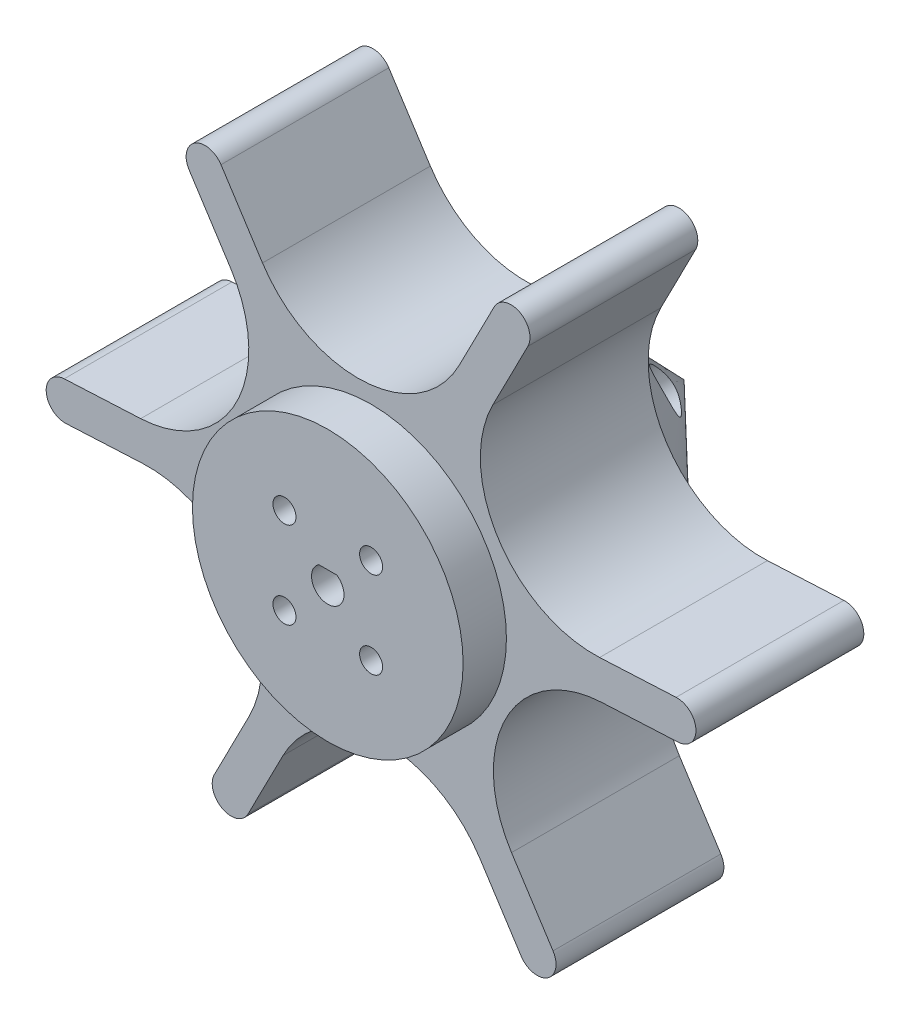
SolidWorks part; units mm, degrees
ref_plane "Front Plane" through (0, 0, 0) normal (0, 0, 1) x (1, 0, 0)
ref_plane "Top Plane" through (0, 0, 0) normal (0, 1, 0) x (1, 0, 0)
ref_plane "Right Plane" through (0, 0, 0) normal (1, 0, 0) x (0, 0, -1)
sketch "Sketch1" plane through (0, 0, 0) normal (0, 0, 1) x (1, 0, 0)
  line L0 (-33.6058, 45.6534) -> (-25.9397, 33.7658)
  line L1 (-30.6644, 47.5503) -> (-56.5119, -2.781) construction
  line L2 (-56.5119, -2.781) -> (-25.8475, -50.3313) construction
  line L3 (-25.8475, -50.3313) -> (30.6644, -47.5503) construction
  line L4 (30.6644, -47.5503) -> (56.5119, 2.781) construction
  line L5 (56.5119, 2.781) -> (25.8475, 50.3313) construction
  line L6 (25.8475, 50.3313) -> (-30.6644, 47.5503) construction
  line L7 (-27.723, 49.4471) -> (-20.0569, 37.5596)
  line L8 (22.7341, 51.9302) -> (16.2722, 39.3474)
  line L9 (28.961, 48.7324) -> (22.4991, 36.1496)
  line L10 (56.3399, 6.2768) -> (42.2119, 5.5815)
  line L11 (56.684, -0.7147) -> (42.556, -1.41)
  line L12 (33.6058, -45.6534) -> (25.9397, -33.7658)
  line L13 (27.723, -49.4471) -> (20.0569, -37.5596)
  line L14 (-22.7341, -51.9302) -> (-16.2722, -39.3474)
  line L15 (-28.961, -48.7324) -> (-22.4991, -36.1496)
  line L16 (-56.3399, -6.2768) -> (-42.2119, -5.5815)
  line L17 (-56.684, 0.7147) -> (-42.556, 1.41)
  circle A0 centre (41.1797, 26.5562) radius 21 construction
  circle A1 centre (43.5882, -22.3846) radius 21 construction
  circle A2 centre (2.4085, -48.9408) radius 21 construction
  circle A3 centre (-41.1797, -26.5562) radius 21 construction
  circle A4 centre (-43.5882, 22.3846) radius 21 construction
  circle A5 centre (-2.4085, 48.9408) radius 21 construction
  circle A6 centre (0, 0) radius 49 construction
  circle A7 centre (-30.6644, 47.5503) radius 3.5
  circle A8 centre (25.8475, 50.3313) radius 3.5
  circle A9 centre (56.5119, 2.781) radius 3.5
  circle A10 centre (30.6644, -47.5503) radius 3.5
  circle A11 centre (-25.8475, -50.3313) radius 3.5
  circle A12 centre (-56.5119, -2.781) radius 3.5
  arc A13 (-42.556, 1.41) -> (-25.9397, 33.7658) centre (-43.5882, 22.3846) ccw
  arc A14 (-20.0569, 37.5596) -> (16.2722, 39.3474) centre (-2.4085, 48.9408) ccw
  arc A15 (22.4991, 36.1496) -> (42.2119, 5.5815) centre (41.1797, 26.5562) ccw
  arc A16 (42.556, -1.41) -> (25.9397, -33.7658) centre (43.5882, -22.3846) ccw
  arc A17 (20.0569, -37.5596) -> (-16.2722, -39.3474) centre (2.4085, -48.9408) ccw
  arc A18 (-22.4991, -36.1496) -> (-42.2119, -5.5815) centre (-41.1797, -26.5562) ccw
  point P25 (0, 0)
  point P36 (0, 0)
  point P60 (0, 0)
  point P77 (0, 0)
  dimension "D2" = 42
  dimension "D4" = 7
  dimension "D1" = 6
  dimension "D3" = 6
  dimension "D5" = 6
  dimension "D6" = 6
extrude "Boss-Extrude1" add sketch "Sketch1" along normal blind 21 contours A18 L15 A11 L14 A17 L13 A10 L12 A16 L11 A9 L10 A15 L9 A8 L8 A14 L7 A7 L0 A13 L17 A12 L16 | A12 | A7 | A8 | A9 | A10 | A11
ref_plane "Plane1" through (0, 0, 0) normal (0.0492, -0.9988, 0) x (-0.9988, -0.0492, 0)
sketch "Sketch3" plane through (0, 0, 0) normal (0.0492, -0.9988, 0) x (-0.9988, -0.0492, 0)
  line L0 (0, 0) -> (-28, 0)
  line L1 (-28, 0) -> (0, 26.8135)
  line L2 (0, 26.8135) -> (0, 0)
  dimension "D1" = 28
revolve "Revolve1" add sketch "Sketch3" angle 360 about L2
sketch "Sketch4" plane through (0, 0, 21) normal (0, 0, 1) x (1, 0, 0)
  circle A0 centre (0, 0) radius 25
  dimension "D1" = 50
extrude "Boss-Extrude2" add sketch "Sketch4" along normal blind 18
sketch "Sketch5" plane through (0, 0, 39) normal (0, 0, 1) x (1, 0, 0)
  line L0 (-1.6583, 2.5) -> (1.6583, 2.5)
  arc A0 (-1.6583, 2.5) -> (1.6583, 2.5) centre (0, 0) ccw
  dimension "D1" = 6
  dimension "D2" = 2.5
extrude "Cut-Extrude2" cut sketch "Sketch5" against normal blind 20
ref_plane "Plane2" through (-1.2288, 24.9698, 0) normal (-0.0492, 0.9988, 0) x (0.9988, 0.0492, 0)
ref_plane "Plane5" through (1.2288, -24.9698, 0) normal (0.0492, -0.9988, 0) x (-0.9988, -0.0492, 0)
sketch "Sketch7" plane through (0, 0, 39) normal (0, 0, 1) x (1, 0, 0)
  line L0 (0, 12.9158) -> (0, -15.3556) construction
  line L1 (-12.6694, 0) -> (16.084, 0) construction
  circle A0 centre (-8, 8) radius 2.125
  circle A1 centre (8, 8) radius 2.125
  circle A2 centre (8, -8) radius 2.125
  circle A3 centre (-8, -8) radius 2.125
  dimension "D1" = 4.25
  dimension "D2" = 8
  dimension "D3" = 8
extrude "Cut-Extrude3" cut sketch "Sketch7" against normal through all
sketch "Sketch9" plane through (0, 0, 0) normal (0, 0, -1) x (-1, 0, 0)
  line L0 (0, 0) -> (24.2952, 0) construction
  line L1 (0, 0) -> (0, 21.4598) construction
  circle A1 centre (-8, 8) radius 2.125 construction
  circle A5 centre (-8, 8) radius 2.125 construction
  circle A8 centre (-8, 8) radius 4
  circle A10 centre (8, 8) radius 4
  circle A11 centre (8, -8) radius 4
  circle A12 centre (-8, -8) radius 4
  dimension "D1" = 8
extrude "Cut-Extrude4" cut sketch "Sketch9" against normal offset from surface 3 and the other way through all up to face at (-10.125, -8, 39)
sketch "Sketch10" plane through (0, 0, 21) normal (0, 0, 1) x (1, 0, 0)
  line L0 (-1.6583, 2.5) -> (1.6583, 2.5) construction
  line L1 (-1.6583, 2.5) -> (1.6583, 2.5)
  line L12 (-22.4991, -36.1496) -> (-28.961, -48.7324)
  line L13 (-22.7341, -51.9302) -> (-16.2722, -39.3474)
  line L14 (20.0569, -37.5596) -> (27.723, -49.4471)
  line L15 (33.6058, -45.6534) -> (25.9397, -33.7658)
  line L16 (42.556, -1.41) -> (56.684, -0.7147)
  line L17 (56.3399, 6.2768) -> (42.2119, 5.5815)
  line L18 (22.4991, 36.1496) -> (28.961, 48.7324)
  line L19 (22.7341, 51.9302) -> (16.2722, 39.3474)
  line L20 (-20.0569, 37.5596) -> (-27.723, 49.4471)
  line L21 (-33.6058, 45.6534) -> (-25.9397, 33.7658)
  line L22 (-42.556, 1.41) -> (-56.684, 0.7147)
  line L23 (-56.3399, -6.2768) -> (-42.2119, -5.5815)
  line L24 (-22.4991, -36.1496) -> (-28.961, -48.7324)
  line L25 (-22.7341, -51.9302) -> (-16.2722, -39.3474)
  line L26 (20.0569, -37.5596) -> (27.723, -49.4471)
  line L27 (33.6058, -45.6534) -> (25.9397, -33.7658)
  line L28 (42.556, -1.41) -> (56.684, -0.7147)
  line L29 (56.3399, 6.2768) -> (42.2119, 5.5815)
  line L30 (22.4991, 36.1496) -> (28.961, 48.7324)
  line L31 (22.7341, 51.9302) -> (16.2722, 39.3474)
  line L32 (-20.0569, 37.5596) -> (-27.723, 49.4471)
  line L33 (-33.6058, 45.6534) -> (-25.9397, 33.7658)
  line L34 (-42.556, 1.41) -> (-56.684, 0.7147)
  line L35 (-56.3399, -6.2768) -> (-42.2119, -5.5815)
  circle A0 centre (8, -8) radius 2.125 construction
  arc A1 (-1.6583, 2.5) -> (1.6583, 2.5) centre (0, 0) ccw construction
  circle A2 centre (-8, -8) radius 2.125 construction
  circle A3 centre (8, 8) radius 2.125 construction
  circle A4 centre (-8, 8) radius 2.125 construction
  circle A5 centre (8, -8) radius 2.125
  arc A6 (-1.6583, 2.5) -> (1.6583, 2.5) centre (0, 0) ccw
  circle A7 centre (-8, -8) radius 2.125
  circle A8 centre (8, 8) radius 2.125
  circle A9 centre (-8, 8) radius 2.125
  arc A12 (-22.4991, -36.1496) -> (-42.2119, -5.5815) centre (-41.1797, -26.5562) ccw
  arc A13 (-28.961, -48.7324) -> (-22.7341, -51.9302) centre (-25.8475, -50.3313) ccw
  arc A14 (20.0569, -37.5596) -> (-16.2722, -39.3474) centre (2.4085, -48.9408) ccw
  arc A15 (27.723, -49.4471) -> (33.6058, -45.6534) centre (30.6644, -47.5503) ccw
  arc A16 (42.556, -1.41) -> (25.9397, -33.7658) centre (43.5882, -22.3846) ccw
  arc A17 (56.684, -0.7147) -> (56.3399, 6.2768) centre (56.5119, 2.781) ccw
  arc A18 (22.4991, 36.1496) -> (42.2119, 5.5815) centre (41.1797, 26.5562) ccw
  arc A19 (28.961, 48.7324) -> (22.7341, 51.9302) centre (25.8475, 50.3313) ccw
  arc A20 (-20.0569, 37.5596) -> (16.2722, 39.3474) centre (-2.4085, 48.9408) ccw
  arc A21 (-27.723, 49.4471) -> (-33.6058, 45.6534) centre (-30.6644, 47.5503) ccw
  arc A22 (-42.556, 1.41) -> (-25.9397, 33.7658) centre (-43.5882, 22.3846) ccw
  arc A23 (-56.684, 0.7147) -> (-56.3399, -6.2768) centre (-56.5119, -2.781) ccw
  arc A24 (-22.4991, -36.1496) -> (-42.2119, -5.5815) centre (-41.1797, -26.5562) ccw
  arc A25 (-28.961, -48.7324) -> (-22.7341, -51.9302) centre (-25.8475, -50.3313) ccw
  arc A26 (20.0569, -37.5596) -> (-16.2722, -39.3474) centre (2.4085, -48.9408) ccw
  arc A27 (27.723, -49.4471) -> (33.6058, -45.6534) centre (30.6644, -47.5503) ccw
  arc A28 (42.556, -1.41) -> (25.9397, -33.7658) centre (43.5882, -22.3846) ccw
  arc A29 (56.684, -0.7147) -> (56.3399, 6.2768) centre (56.5119, 2.781) ccw
  arc A30 (22.4991, 36.1496) -> (42.2119, 5.5815) centre (41.1797, 26.5562) ccw
  arc A31 (28.961, 48.7324) -> (22.7341, 51.9302) centre (25.8475, 50.3313) ccw
  arc A32 (-20.0569, 37.5596) -> (16.2722, 39.3474) centre (-2.4085, 48.9408) ccw
  arc A33 (-27.723, 49.4471) -> (-33.6058, 45.6534) centre (-30.6644, 47.5503) ccw
  arc A34 (-42.556, 1.41) -> (-25.9397, 33.7658) centre (-43.5882, 22.3846) ccw
  arc A35 (-56.684, 0.7147) -> (-56.3399, -6.2768) centre (-56.5119, -2.781) ccw
  dimension "D1" = 0
extrude "Boss-Extrude3" add sketch "Sketch10" along normal blind 10
